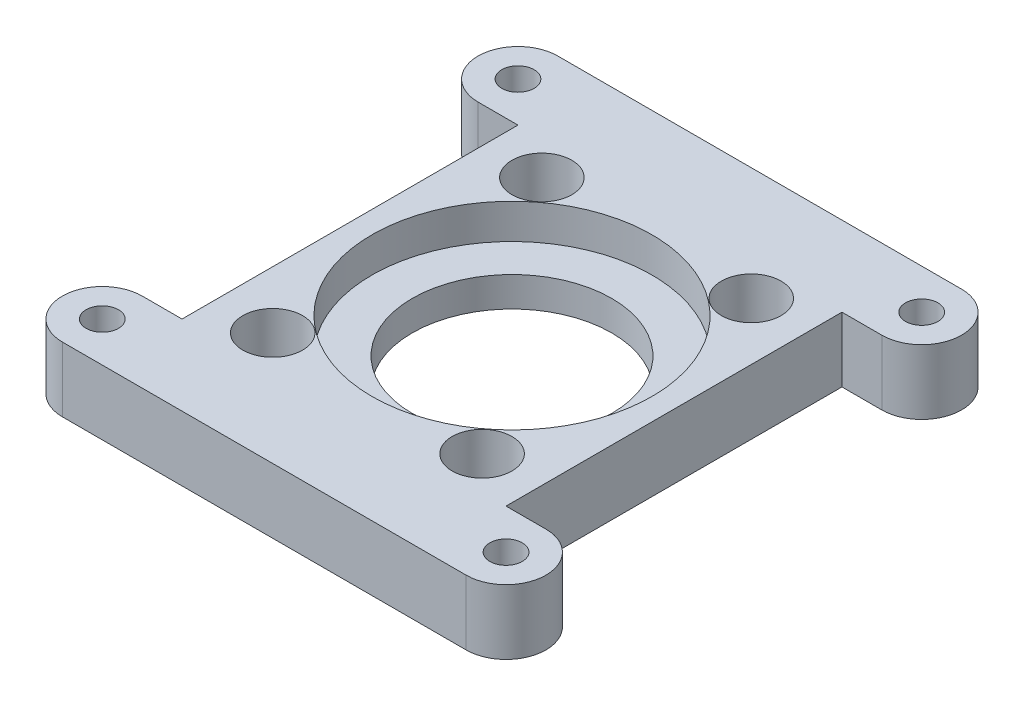
SolidWorks part; units mm, degrees
ref_plane "Front Plane" through (0, 0, 0) normal (0, 0, 1) x (1, 0, 0)
ref_plane "Top Plane" through (0, 0, 0) normal (0, 1, 0) x (1, 0, 0)
ref_plane "Right Plane" through (0, 0, 0) normal (1, 0, 0) x (0, 0, -1)
sketch "Sketch1" plane through (0, 0, 0) normal (0, 1, 0) x (1, 0, 0)
  line L1 (15, -16.85) -> (-15, -16.85)
  line L2 (15, -16.85) -> (15, 16.85)
  line L3 (15, 16.85) -> (-15, 16.85)
  line L4 (-15, -16.85) -> (-15, 16.85)
  line L5 (15, -16.85) -> (-15, 16.85) construction
  line L6 (15, 16.85) -> (-15, -16.85) construction
  circle A0 centre (-11.75, 13.5) radius 1.375
  circle A1 centre (-11.75, -13.5) radius 1.375
  circle A2 centre (9.25, -13.5) radius 1.4608
  circle A3 centre (9.25, 13.5) radius 1.4807
  circle A4 centre (-1.25, 0) radius 14
  point P0 (0, 0)
  dimension "D3" = 27
  dimension "D4" = 2.75
  dimension "D5" = 2.75
  dimension "D6" = 3.35
  dimension "D7" = 3.25
  dimension "D8" = 3.25
  dimension "D9" = 21
  dimension "D10" = 21
  dimension "D11" = 3.35
  dimension "D12" = 3.35
  dimension "D13" = 28
  dimension "D14" = 13.75
  dimension "D1" = 33.7
  dimension "D2" = 30
extrude "Boss-Extrude1" add sketch "Sketch1" along normal blind 15 contours A4 L4 L1 L2 L3 A3 A2 A1 A0
sketch "Sketch2" plane through (0, 15, 0) normal (0, 1, 0) x (1, 0, 0)
  circle A0 centre (-1.25, 0) radius 14
  circle A1 centre (-1.25, 0) radius 10
  dimension "D1" = 20
extrude "Boss-Extrude2" add sketch "Sketch2" against normal blind 8
sketch "Sketch3" plane through (0, 15, 0) normal (0, 1, 0) x (1, 0, 0)
  circle A0 centre (-1.25, 0) radius 14
  circle A1 centre (-1.25, 0) radius 10
extrude "Cut-Extrude1" cut sketch "Sketch3" against normal blind 3
sketch "Sketch5" plane through (0, 15, 0) normal (0, 1, 0) x (1, 0, 0)
  line L1 (15, -16.85) -> (-15, -16.85)
  line L2 (15, -16.85) -> (15, 16.85)
  line L3 (15, 16.85) -> (-15, 16.85)
  line L4 (-15, -16.85) -> (-15, 16.85)
  line L5 (15, -16.85) -> (-15, 16.85) construction
  line L6 (15, 16.85) -> (-15, -16.85) construction
  circle A0 centre (-1.25, 0) radius 14
  circle A1 centre (-11.75, 13.5) radius 1.375
  circle A2 centre (9.25, 13.5) radius 1.4807
  circle A3 centre (9.25, -13.5) radius 1.4608
  circle A4 centre (-11.75, -13.5) radius 1.375
  point P3 (0, 0)
  arc M1 (-15, 2.6339) -> (-15, -2.6339) centre (-1.25, 0) cw
  line M2 (-15, -2.6339) -> (-15, -16.85)
  line M3 (-15, -16.85) -> (15, -16.85)
  line M4 (15, -16.85) -> (15, 16.85)
  line M5 (15, 16.85) -> (-15, 16.85)
  line M6 (-15, 16.85) -> (-15, 2.6339)
  circle M7 centre (9.25, 13.5) radius 1.4807
  circle M8 centre (9.25, -13.5) radius 1.4608
  circle M9 centre (-11.75, -13.5) radius 1.375
  circle M10 centre (-11.75, 13.5) radius 1.375
extrude "Boss-Extrude3" add sketch "Sketch5" along normal blind 0.5 contours M6 M1 M2 M3 M4 M5 M7 M9 M10 M8
sketch "Sketch6" plane through (0, 0, 0) normal (0, -1, 0) x (1, 0, 0)
  line L1 (16.2077, -17.3573) -> (-16.2077, -17.3573)
  line L2 (16.2077, -17.3573) -> (16.2077, 17.3573)
  line L3 (16.2077, 17.3573) -> (-16.2077, 17.3573)
  line L4 (-16.2077, -17.3573) -> (-16.2077, 17.3573)
  line L5 (16.2077, -17.3573) -> (-16.2077, 17.3573) construction
  line L6 (16.2077, 17.3573) -> (-16.2077, -17.3573) construction
  point P0 (0, 0)
extrude "Cut-Extrude2" cut sketch "Sketch6" against normal blind 7
sketch "Sketch7" plane through (0, 7, 0) normal (0, -1, 0) x (1, 0, 0)
  line L1 (16.7176, -17.9135) -> (-16.7176, -17.9135)
  line L2 (16.7176, -17.9135) -> (16.7176, 17.9135)
  line L3 (16.7176, 17.9135) -> (-16.7176, 17.9135)
  line L4 (-16.7176, -17.9135) -> (-16.7176, 17.9135)
  line L5 (16.7176, -17.9135) -> (-16.7176, 17.9135) construction
  line L6 (16.7176, 17.9135) -> (-16.7176, -17.9135) construction
  point P0 (0, 0)
extrude "Cut-Extrude3" cut sketch "Sketch7" against normal blind 2
sketch "Sketch8" plane through (0, 9, 0) normal (0, -1, 0) x (1, 0, 0)
  line L0 (-15, 16.85) -> (15, 16.85) construction
  line L1 (-15, -16.85) -> (15, -16.85) construction
  line L3 (-3.5, 20.35) -> (3.5, 20.35)
  line L4 (-3.5, 20.35) -> (-3.5, -20.35)
  line L5 (-3.5, -20.35) -> (3.5, -20.35)
  line L6 (3.5, 20.35) -> (3.5, -20.35)
  circle A0 centre (0, 20.35) radius 1.625
  circle A1 centre (0, -20.35) radius 1.625
  circle A2 centre (0, 20.35) radius 3.5
  circle A3 centre (0, -20.35) radius 3.5
  line M7 (-15, -16.85) -> (15, -16.85)
  line M9 (15, 16.85) -> (-15, 16.85)
  dimension "D1" = 3.25
  dimension "D2" = 3.25
  dimension "D3" = 7
  dimension "D4" = 7
  dimension "D5" = 3.5
  dimension "D6" = 3.5
extrude "Boss-Extrude4" add sketch "Sketch8" against normal blind 6.5 contours A2 L6 M9 | A2 L4 M9 | A2 L3 A0 | L3 A2 A0 | A3 L6 M7 | A3 L4 M7 | L5 A3 A1 | L5 A3 A1
sketch "Sketch9" plane through (0, 9, 0) normal (0, -1, 0) x (1, 0, 0)
  circle A0 centre (0, 20.35) radius 1.625
  circle A1 centre (0, 20.35) radius 3.5
  circle A2 centre (0, -20.35) radius 1.625
  circle A3 centre (0, -20.35) radius 3.5
extrude "Cut-Extrude4" cut sketch "Sketch9" against normal blind 3
sketch "Sketch10" plane through (0, 9, 0) normal (0, -1, 0) x (1, 0, 0)
  circle A0 centre (-11.75, 13.5) radius 3
  circle A1 centre (9.25, 13.5) radius 3
  circle A2 centre (9.25, -13.5) radius 3
  circle A3 centre (-11.75, -13.5) radius 3
  dimension "D1" = 6
  dimension "D2" = 6
  dimension "D3" = 6
  dimension "D4" = 6
extrude "Cut-Extrude5" cut sketch "Sketch10" against normal blind 28
sketch "Sketch11" plane through (0, 15.5, 0) normal (0, 1, 0) x (1, 0, 0)
  circle A0 centre (-1.25, 0) radius 14.05
  dimension "D1" = 28.1
extrude "Cut-Extrude6" cut sketch "Sketch11" against normal blind 3.5
sketch "Sketch12" plane through (0, 15.5, 0) normal (0, 1, 0) x (1, 0, 0)
  line L0 (15, -16.85) -> (15, 16.85) construction
  line L1 (-15, 16.85) -> (15, 16.85)
  line L2 (-15, 16.85) -> (-15, 24.85)
  line L3 (-15, 24.85) -> (15, 24.85)
  line L4 (15, 16.85) -> (15, 24.85)
  line L5 (-15, -16.85) -> (15, -16.85)
  line L6 (-15, -16.85) -> (-15, -24.8456)
  line L7 (-15, -24.8456) -> (15, -24.8456)
  line L8 (15, -16.85) -> (15, -24.8456)
  dimension "D1" = 0
  dimension "D2" = 8
  dimension "D3" = 0
  dimension "D4" = 7.9956
extrude "Boss-Extrude5" add sketch "Sketch12" against normal blind 6.5
sketch "Sketch13" plane through (0, 15.5, 0) normal (0, 1, 0) x (1, 0, 0)
  line L0 (-15, -24.8456) -> (15, -24.8456) construction
  line L1 (-15, 24.85) -> (-17.5, 24.85)
  line L2 (-15, 24.85) -> (-15, -24.8456)
  line L3 (-15, -24.8456) -> (-17.5, -24.8456)
  line L4 (-17.5, 24.85) -> (-17.5, -24.8456)
  circle A0 centre (-1.25, 0) radius 14.05
  line M8 (-15, 24.85) -> (-15, 2.8879)
  line M10 (-15, -2.8879) -> (-15, -24.8456)
  dimension "D3" = 28.1
  dimension "D1" = 0
  dimension "D2" = 2.5
extrude "Boss-Extrude8" add sketch "Sketch13" against normal blind 6.5 contours A0 L1 L4 L3 M8 M10
sketch "Sketch15" plane through (0, 9, 0) normal (0, -1, 0) x (1, 0, 0)
  circle A0 centre (-1.25, 0) radius 14
  circle A1 centre (-1.25, 0) radius 14.05
extrude "Boss-Extrude9" add sketch "Sketch15" against normal blind 3
sketch "Sketch16" plane through (0, 15.5, 0) normal (0, 1, 0) x (1, 0, 0)
  line L0 (15, 24.85) -> (-17.5, 24.85) construction
  line L1 (-25.5, 24.85) -> (23, 24.85)
  line L2 (-25.5, 24.85) -> (-25.5, -24.8456)
  line L3 (-25.5, -24.8456) -> (23, -24.8456)
  line L4 (23, 24.85) -> (23, -24.8456)
  line L5 (-17.5, -24.8456) -> (15, -24.8456) construction
  line L6 (15, -24.8456) -> (15, 24.85) construction
  line L7 (-25.5, 16.85) -> (23, 16.85)
  line L8 (-25.5, 16.85) -> (-25.5, -16.8456)
  line L9 (-25.5, -16.8456) -> (23, -16.8456)
  line L10 (23, 16.85) -> (23, -16.8456)
  line L11 (-17.5, 24.85) -> (-17.5, -24.8456) construction
  line L12 (-25.5, 0.0022) -> (23, 0.0022) construction
  circle A0 centre (-21.5, 20.85) radius 4
  circle A1 centre (19, 20.85) radius 4
  circle A2 centre (-21.5, 20.85) radius 1.625
  circle A3 centre (19, 20.85) radius 1.625
  circle A4 centre (19, -20.8456) radius 4
  circle A5 centre (19, -20.8456) radius 1.625
  circle A6 centre (-21.5, -20.8456) radius 1.625
  circle A7 centre (-21.5, -20.8456) radius 4
  line M12 (-17.5, 24.85) -> (-17.5, -24.8456)
  line M14 (15, -24.8456) -> (15, 24.85)
  dimension "D7" = 8
  dimension "D9" = 4
  dimension "D10" = 4
  dimension "D11" = 8
  dimension "D12" = 4
  dimension "D13" = 3.25
  dimension "D14" = 3.25
  dimension "D1" = 0
  dimension "D2" = 0
  dimension "D3" = 8
  dimension "D4" = 8
  dimension "D5" = 8
  dimension "D6" = 8
  dimension "D8" = 4
extrude "Boss-Extrude10" add sketch "Sketch16" against normal blind 6.5 contours A0 L1 M12 | A0 L7 M12 | A0 A2 | A1 A3 | A1 L7 M14 | A1 L1 M14 | L9 A7 M12 | A7 L3 M12 | A7 A6 | A4 L9 M14 | L3 A4 M14 | A4 A5
